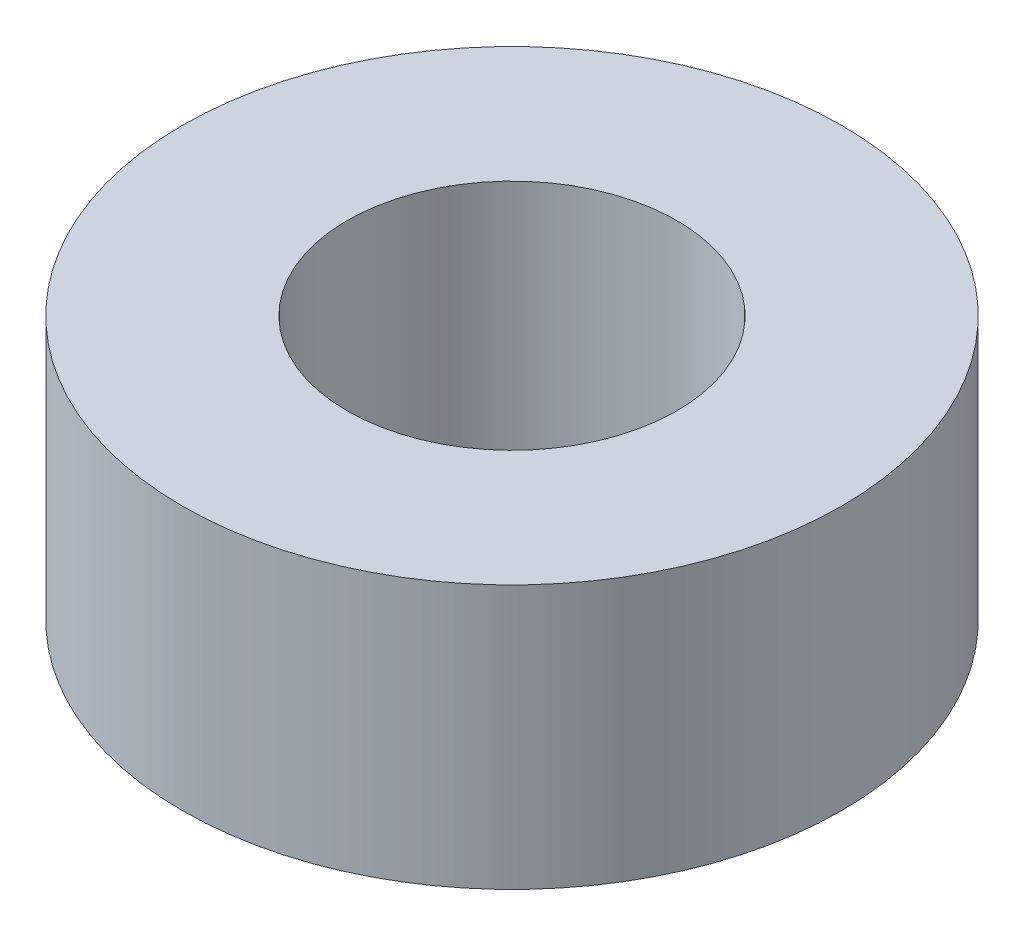
SolidWorks part; units mm, degrees
ref_plane "前视基准面" through (0, 0, 0) normal (0, 0, 1) x (1, 0, 0)
ref_plane "上视基准面" through (0, 0, 0) normal (0, 1, 0) x (1, 0, 0)
ref_plane "右视基准面" through (0, 0, 0) normal (1, 0, 0) x (0, 0, -1)
sketch "Sketch1" plane through (0, 0, 0) normal (0, 1, 0) x (1, 0, 0)
  circle A0 centre (0, 0) radius 2.5
  circle A1 centre (0, 0) radius 5
extrude "Boss-Extrude1" add sketch "Sketch1" along normal blind 4
